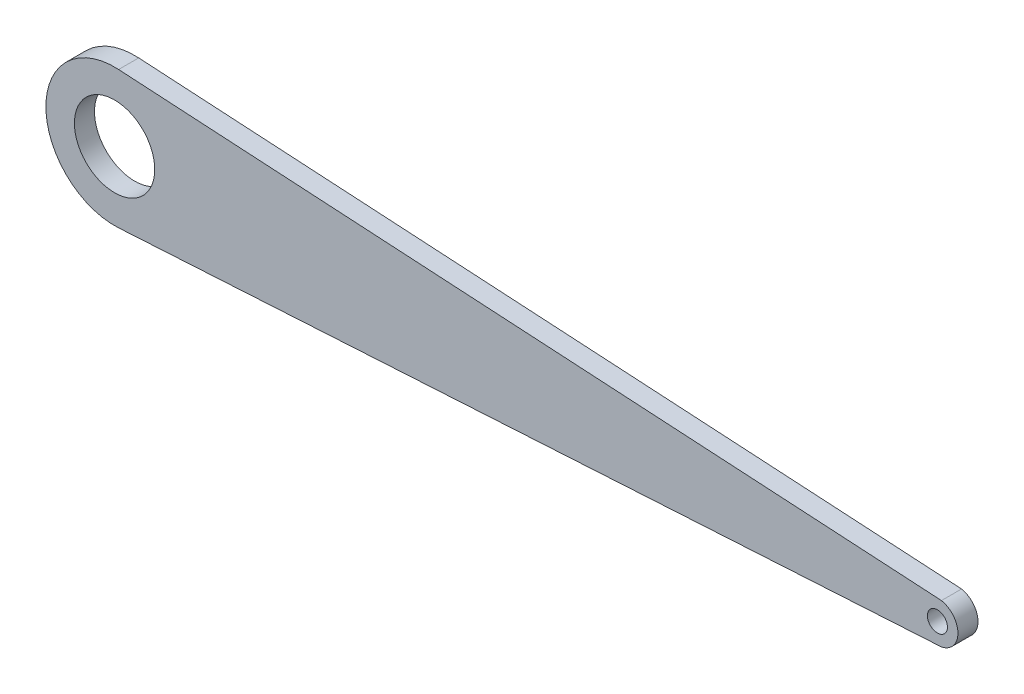
SolidWorks part; units mm, degrees
ref_plane "Plano frontal" through (0, 0, 0) normal (0, 0, 1) x (1, 0, 0)
ref_plane "Plano superior" through (0, 0, 0) normal (0, 1, 0) x (1, 0, 0)
ref_plane "Plano direito" through (0, 0, 0) normal (1, 0, 0) x (0, 0, -1)
sketch "Esboço1" plane through (0, 0, 0) normal (0, 0, 1) x (1, 0, 0)
  line L1 (-24.3251, 0) -> (24.3251, 0) construction
  line L3 (-102.4, -17.0701) -> (102.4, -5)
  line L4 (-102.4, 17.0701) -> (102.4, 5)
  arc A1 (102.4, 5) -> (102.4, -5) centre (101.394, 0) cw
  circle A2 centre (-103.406, 0) radius 10
  circle A3 centre (101.394, 0) radius 2.5
  arc A4 (-102.4, -17.0701) -> (-102.4, 17.0701) centre (-103.406, 0) cw
  point P3 (0, 5)
  dimension "D3" = 20
  dimension "D2" = 0
  dimension "D1" = 204.8
extrude "Ressalto-extrusão1" add sketch "Esboço1" along normal blind 5
